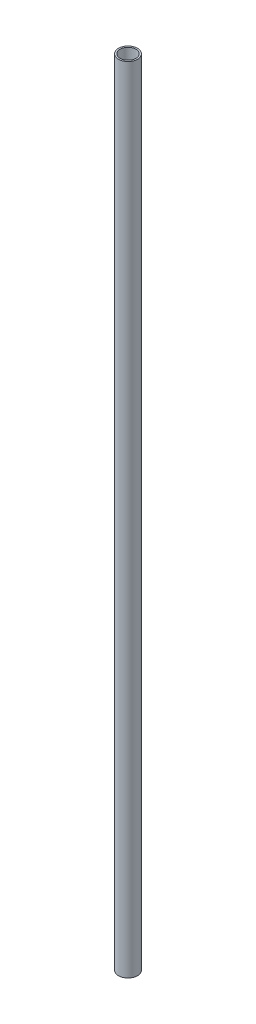
SolidWorks part; units mm, degrees
ref_plane "前视基准面" through (0, 0, 0) normal (0, 0, 1) x (1, 0, 0)
ref_plane "上视基准面" through (0, 0, 0) normal (0, 1, 0) x (1, 0, 0)
ref_plane "右视基准面" through (0, 0, 0) normal (1, 0, 0) x (0, 0, -1)
sketch "草图1" plane through (0, 0, 0) normal (0, 1, 0) x (1, 0, 0)
  circle A0 centre (0, 0) radius 5
  circle A1 centre (0, 0) radius 6
  dimension "D1" = 12
  dimension "D2" = 10
extrude "凸台-拉伸1" add sketch "草图1" along normal blind 500
